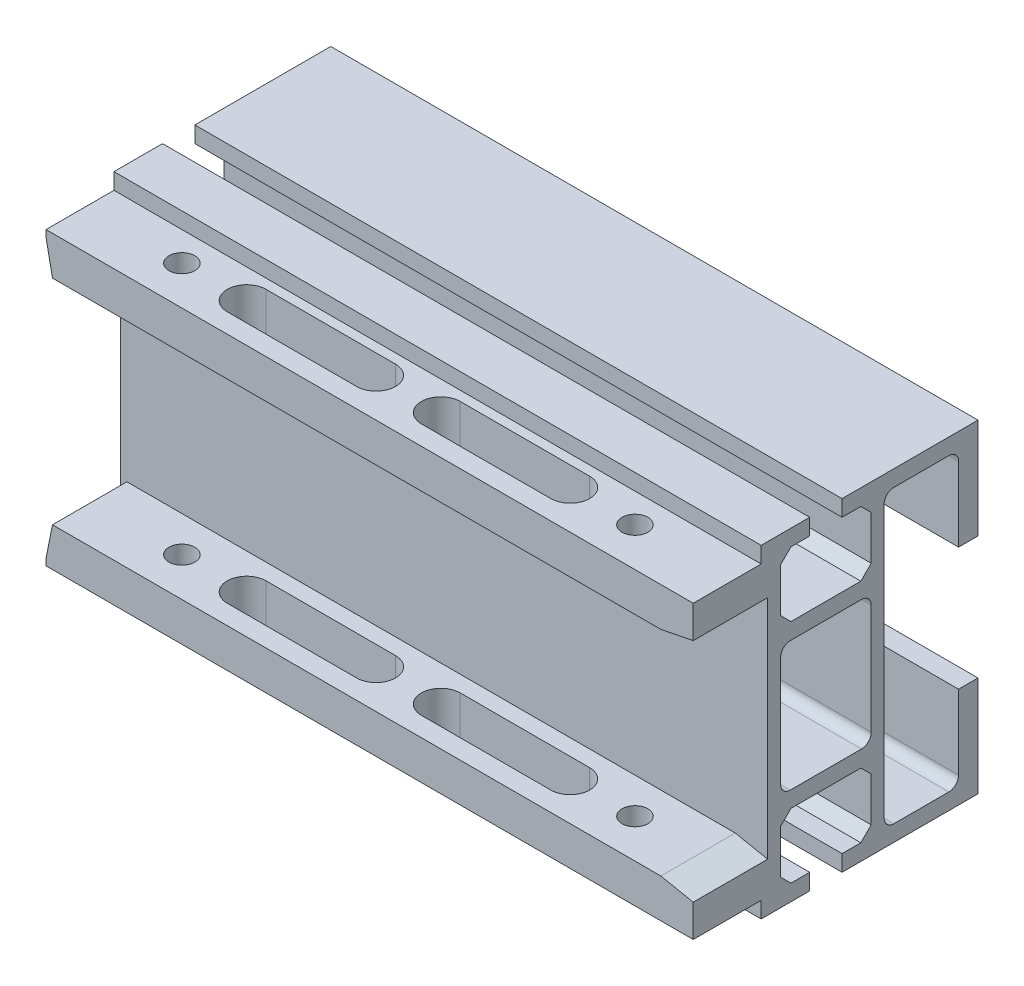
SolidWorks part; units mm, degrees
ref_plane "Piano frontale" through (0, 0, 0) normal (0, 0, 1) x (1, 0, 0)
ref_plane "Piano superiore" through (0, 0, 0) normal (0, 1, 0) x (1, 0, 0)
ref_plane "Piano destro" through (0, 0, 0) normal (1, 0, 0) x (0, 0, -1)
ref_plane "Piano1" through (0, 0, -23.5) normal (0, 0, -1) x (-1, 0, 0)
sketch "Schizzo1" plane through (0, 0, -23.5) normal (0, 0, -1) x (-1, 0, 0)
  line L0 (0, -25) -> (0, 25)
  line L1 (0, 25) -> (-100, 25)
  line L2 (-100, 25) -> (-100, -25)
  line L3 (-100, -25) -> (0, -25)
  dimension "D1" = 100
  dimension "D2" = 50
extrude "Estrusione-Estrusione1" add sketch "Schizzo1" against normal blind 44
sketch "Schizzo2" plane through (0, 0, 0) normal (-1, 0, 0) x (0, 0, 1)
  line L0 (20.5, -22.5) -> (10, -22.5)
  line L1 (10, -22.5) -> (10, -25)
  line L2 (10, -25) -> (20.5, -25)
  line L3 (20.5, -25) -> (20.5, -22.5)
  line L4 (-23.5, -25) -> (-23.5, 25) construction
  line L5 (20.5, -25) -> (-23.5, -25) construction
  dimension "D1" = 33.5
  dimension "D2" = 44
  dimension "D3" = 2.5
extrude "Taglio-Estrusione1" cut sketch "Schizzo2" against normal through all
sketch "Schizzo3" plane through (0, 0, 0) normal (-1, 0, 0) x (0, 0, 1)
  line L0 (-2.5, -25) -> (2.5, -25)
  line L1 (2.5, -25) -> (2.5, -22.5)
  line L2 (2.5, -22.5) -> (7, -22.5)
  line L3 (7, -22.5) -> (7, -12.5)
  line L4 (7, -12.5) -> (-7, -12.5)
  line L5 (-7, -12.5) -> (-7, -22.5)
  line L6 (-7, -22.5) -> (-2.5, -22.5)
  line L7 (-2.5, -22.5) -> (-2.5, -25)
  line L8 (20.5, -22.5) -> (20.5, 25) construction
  line L9 (20.5, -22.5) -> (10, -22.5) construction
  dimension "D1" = 13.5
  dimension "D2" = 18
  dimension "D3" = 23
  dimension "D4" = 27.5
  dimension "D5" = 10
  dimension "D6" = 2.5
extrude "Taglio-Estrusione2" cut sketch "Schizzo3" against normal through all
sketch "Schizzo4" plane through (0, 0, 0) normal (-1, 0, 0) x (0, 0, 1)
  line L0 (-23.5, 9.5) -> (-23.5, -9.5)
  line L1 (-23.5, -9.5) -> (-20.5, -9.5)
  line L2 (-20.5, -9.5) -> (-20.5, -22.5)
  line L3 (-20.5, -22.5) -> (-9, -22.5)
  line L4 (-9, -22.5) -> (-9, 22.5)
  line L5 (-9, 22.5) -> (-20.5, 22.5)
  line L6 (-20.5, 22.5) -> (-20.5, 9.5)
  line L7 (-20.5, 9.5) -> (-23.5, 9.5)
  line L8 (7, -22.5) -> (7, -12.5) construction
  line L9 (7, -12.5) -> (-7, -12.5) construction
  dimension "D1" = 16
  dimension "D2" = 27.5
  dimension "D3" = 30.5
  dimension "D4" = 3
  dimension "D5" = 22
  dimension "D6" = 35
  dimension "D7" = 10
extrude "Taglio-Estrusione3" cut sketch "Schizzo4" against normal through all
sketch "Schizzo5" plane through (0, 0, 0) normal (-1, 0, 0) x (0, 0, 1)
  line L0 (2.5, 25) -> (-2.5, 25)
  line L1 (-2.5, 25) -> (-2.5, 22.5)
  line L2 (-2.5, 22.5) -> (-7, 22.5)
  line L3 (-7, 22.5) -> (-7, 12.5)
  line L4 (-7, 12.5) -> (7, 12.5)
  line L5 (7, 12.5) -> (7, 22.5)
  line L6 (7, 22.5) -> (2.5, 22.5)
  line L7 (2.5, 22.5) -> (2.5, 25)
  line L8 (-23.5, -25) -> (-23.5, -9.5) construction
  line L9 (-2.5, -25) -> (-23.5, -25) construction
  dimension "D1" = 16.5
  dimension "D2" = 21
  dimension "D3" = 26
  dimension "D4" = 30.5
  dimension "D5" = 37.5
  dimension "D6" = 47.5
  dimension "D7" = 50
extrude "Taglio-Estrusione4" cut sketch "Schizzo5" against normal through all
sketch "Schizzo6" plane through (0, 0, 0) normal (-1, 0, 0) x (0, 0, 1)
  line L0 (10, 25) -> (10, 22.5)
  line L1 (10, 22.5) -> (20.5, 22.5)
  line L2 (20.5, 22.5) -> (20.5, 25)
  line L3 (20.5, 25) -> (10, 25)
  line L4 (-20.5, -9.5) -> (-20.5, -22.5) construction
  line L5 (-20.5, -22.5) -> (-9, -22.5) construction
  dimension "D1" = 30.5
  dimension "D2" = 41
  dimension "D3" = 45
  dimension "D4" = 47.5
extrude "Taglio-Estrusione5" cut sketch "Schizzo6" against normal through all
sketch "Schizzo7" plane through (0, 0, 0) normal (-1, 0, 0) x (0, 0, 1)
  line L0 (20.5, -16.5) -> (20.5, 16.5)
  line L1 (20.5, 16.5) -> (9, 16.5)
  line L2 (9, 16.5) -> (9, -16.5)
  line L3 (9, -16.5) -> (20.5, -16.5)
  line L4 (-23.5, 9.5) -> (-23.5, 25) construction
  line L5 (-2.5, 25) -> (-23.5, 25) construction
  dimension "D1" = 32.5
  dimension "D2" = 44
  dimension "D3" = 8.5
  dimension "D4" = 41.5
extrude "Taglio-Estrusione6" cut sketch "Schizzo7" against normal through all
sketch "Schizzo8" plane through (0, 22.5, 0) normal (0, 1, 0) x (-1, 0, 0)
  line L0 (-75, 11.5) -> (-55, 11.5)
  line L1 (-55, 17.5) -> (-75, 17.5)
  line L2 (0, 10) -> (0, 20.5) construction
  line L3 (-100, 20.5) -> (0, 20.5) construction
  arc A0 (-75, 17.5) -> (-75, 11.5) centre (-75, 14.5) ccw
  arc A1 (-55, 11.5) -> (-55, 17.5) centre (-55, 14.5) ccw
  dimension "D1" = 3
  dimension "D2" = 55
  dimension "D3" = 75
  dimension "D4" = 6
extrude "Taglio-Estrusione7" cut sketch "Schizzo8" against normal up to next
sketch "Schizzo9" plane through (0, 22.5, 0) normal (0, 1, 0) x (-1, 0, 0)
  line L0 (-25, 17.5) -> (-45, 17.5)
  line L1 (-45, 11.5) -> (-25, 11.5)
  line L2 (-55, 17.5) -> (-75, 17.5) construction
  arc A0 (-25, 11.5) -> (-25, 17.5) centre (-25, 14.5) ccw
  arc A1 (-45, 17.5) -> (-45, 11.5) centre (-45, 14.5) ccw
  dimension "D1" = 3
  dimension "D2" = 10
  dimension "D3" = 30
  dimension "D4" = 3
extrude "Taglio-Estrusione8" cut sketch "Schizzo9" against normal up to next
sketch "Schizzo10" plane through (0, -22.5, 0) normal (0, -1, 0) x (1, 0, 0)
  line L0 (55, 11.5) -> (75, 11.5)
  line L1 (75, 17.5) -> (55, 17.5)
  line L2 (0, 20.5) -> (0, 10) construction
  line L3 (100, 10) -> (0, 10) construction
  arc A0 (55, 17.5) -> (55, 11.5) centre (55, 14.5) ccw
  arc A1 (75, 11.5) -> (75, 17.5) centre (75, 14.5) ccw
  dimension "D1" = 3
  dimension "D2" = 55
  dimension "D3" = 75
  dimension "D4" = 4.5
extrude "Taglio-Estrusione9" cut sketch "Schizzo10" against normal up to next
sketch "Schizzo11" plane through (0, -22.5, 0) normal (0, -1, 0) x (1, 0, 0)
  line L0 (45, 17.5) -> (25, 17.5)
  line L1 (25, 11.5) -> (45, 11.5)
  line L2 (75, 17.5) -> (55, 17.5) construction
  arc A0 (45, 11.5) -> (45, 17.5) centre (45, 14.5) ccw
  arc A1 (25, 17.5) -> (25, 11.5) centre (25, 14.5) ccw
  dimension "D1" = 3
  dimension "D2" = 10
  dimension "D3" = 30
  dimension "D4" = 3
extrude "Taglio-Estrusione10" cut sketch "Schizzo11" against normal up to next
sketch "Schizzo12" plane through (0, 0, 0) normal (-1, 0, 0) x (0, 0, 1)
  line L0 (7, -10) -> (7, 10)
  line L1 (7, 10) -> (-7, 10)
  line L2 (-7, 10) -> (-7, -10)
  line L3 (-7, -10) -> (7, -10)
  line L4 (9, 16.5) -> (9, -16.5) construction
  line L5 (9, -16.5) -> (20.5, -16.5) construction
  dimension "D1" = 2
  dimension "D2" = 16
  dimension "D3" = 6.5
  dimension "D4" = 26.5
extrude "Taglio-Estrusione11" cut sketch "Schizzo12" against normal through all
hole_wizard "Foro Ø4.0 (4)-1" positions "Schizzo14" profile "Schizzo13" hole size "Ø4.0" standard "Ansi Metric"
sketch "Schizzo14" plane through (0, 16.5, 0) normal (0, -1, 0) x (-1, 0, 0)
  point P0 (-85, -14.5)
  point P1 (-15, -14.5)
sketch "Schizzo13" plane through (85, 16.5, 14.5) normal (1, 0, 0) x (0, 0, -1)
  line L0 (0, 0) -> (0, 8.5)
  line L1 (0, 8.5) -> (2, 8.5)
  line L2 (2, 8.5) -> (2, 0)
  line L5 (2, 0) -> (0, 0)
  line L11 (0, -6.35) -> (0, 107.95) construction
  dimension "Thru Hole Dia." = 4
  dimension "Thru Hole Depth" = 8.5
hole_wizard "Foro Ø4.0 (4)-2" positions "Schizzo16" profile "Schizzo15" hole size "Ø4.0" standard "Ansi Metric"
sketch "Schizzo16" plane through (0, -22.5, 0) normal (0, -1, 0) x (-1, 0, 0)
  point P0 (-85, -14.5)
  point P1 (-15, -14.5)
sketch "Schizzo15" plane through (85, -22.5, 14.5) normal (1, 0, 0) x (0, 0, -1)
  line L0 (0, 0) -> (0, 47.5)
  line L1 (0, 47.5) -> (2, 47.5)
  line L2 (2, 47.5) -> (2, 0)
  line L5 (2, 0) -> (0, 0)
  line L11 (0, -6.35) -> (0, 107.95) construction
  dimension "Thru Hole Dia." = 4
  dimension "Thru Hole Depth" = 47.5
chamfer "Smusso1" distance 5 angle 11.31 2 edges at (0, -16.5, 14.75) (100, 16.5, 14.75)
chamfer "Smusso2" distance 1.6 angle 45 8 edges at (50, 12.5, 7) (50, 22.5, -7) (50, -12.5, 7) (50, -12.5, -7) (50, 12.5, -7) (50, 22.5, 7) (50, -22.5, -7) (50, -22.5, 7)
chamfer "Smusso3" distance 1 angle 78.69 2 edges at (0, 16.5, 14.75) (100, -16.5, 14.75)
fillet "Raccordo1" radius 1.5 8 edges at (50, -10, 7) (50, 22.5, -9) (50, -22.5, -9) (50, 10, 7) (50, 22.5, -20.5) (50, -10, -7) (50, -22.5, -20.5) (50, 10, -7)
